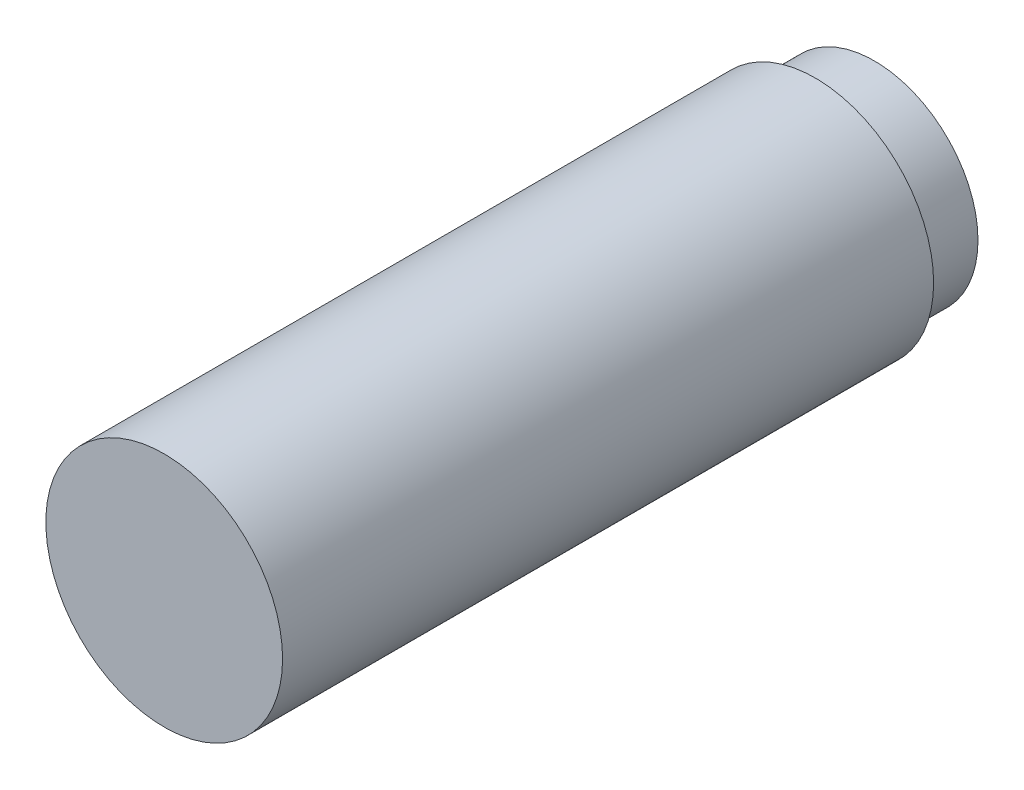
SolidWorks part; units mm, degrees
ref_plane "Front Plane" through (0, 0, 0) normal (0, 0, 1) x (1, 0, 0)
ref_plane "Top Plane" through (0, 0, 0) normal (0, 1, 0) x (1, 0, 0)
ref_plane "Right Plane" through (0, 0, 0) normal (1, 0, 0) x (0, 0, -1)
sketch "Sketch1" plane through (0, 0, 0) normal (0, 0, 1) x (1, 0, 0)
  circle A0 centre (0, 0) radius 25.4
  dimension "D1" = 50.8
extrude "Boss-Extrude2" add sketch "Sketch1" against normal blind 152.4 from offset 76.2 contours A0
sketch "Sketch2" plane through (0, 0, -76.2) normal (0, 0, -1) x (-1, 0, 0)
  circle A0 centre (0, 0) radius 22.225
  circle A1 centre (0, 0) radius 25.4
extrude "Cut-Extrude1" cut sketch "Sketch2" against normal blind 12.7
